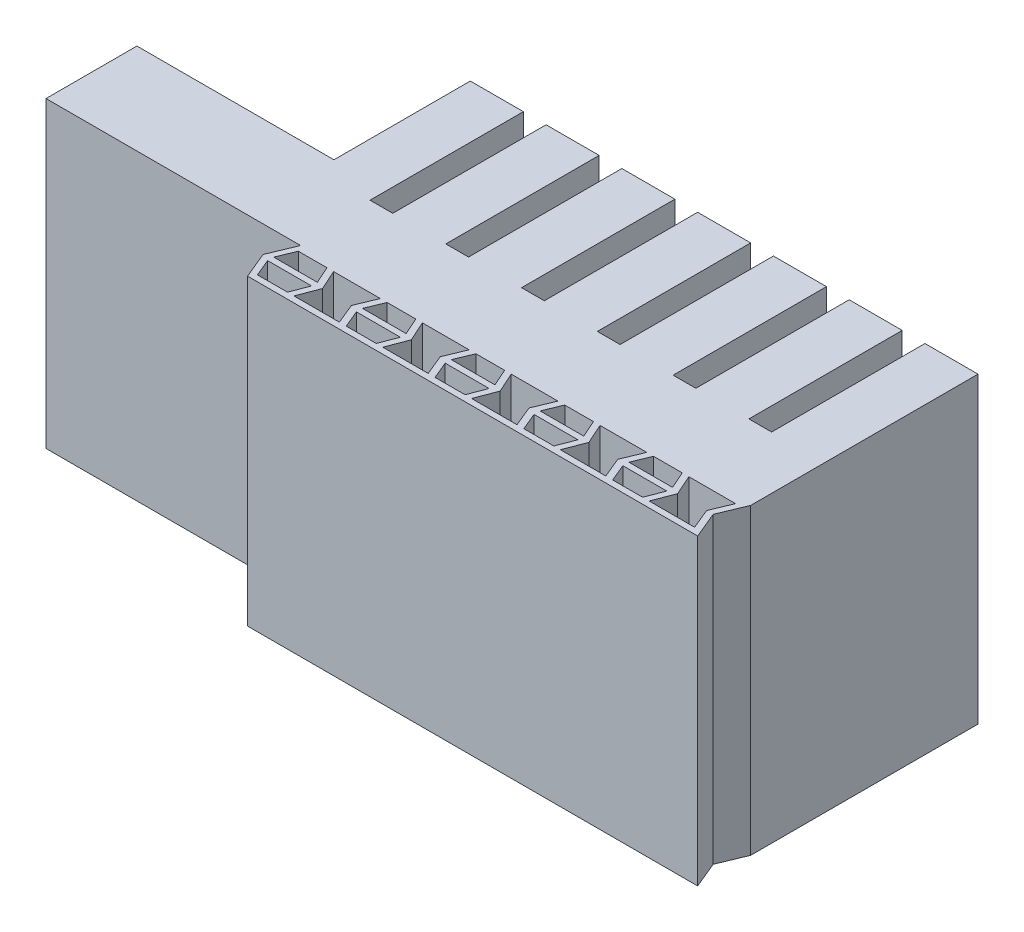
SolidWorks part; units mm, degrees
ref_plane "Front Plane" through (0, 0, 0) normal (0, 0, 1) x (1, 0, 0)
ref_plane "Top Plane" through (0, 0, 0) normal (0, 1, 0) x (1, 0, 0)
ref_plane "Right Plane" through (0, 0, 0) normal (1, 0, 0) x (0, 0, -1)
sketch "Sketch2" plane through (0, 0, 0) normal (0, 1, 0) x (1, 0, 0)
  line L0 (36, 15) -> (36, 4.8815)
  line L1 (0, 0) -> (39.5, 0)
  line L2 (0, 0) -> (0, 6)
  line L4 (39.5, 0) -> (39.5, 15)
  line L5 (34.5, 15) -> (34.5, 4.8815)
  line L6 (31, 15) -> (31, 4.8815)
  line L7 (29.5, 15) -> (29.5, 4.8815)
  line L8 (26, 15) -> (26, 4.8815)
  line L9 (24.5, 15) -> (24.5, 4.8815)
  line L10 (21, 15) -> (21, 4.8815)
  line L11 (19.5, 15) -> (19.5, 4.8815)
  line L12 (16, 15) -> (16, 4.8815)
  line L13 (14.5, 15) -> (14.5, 4.8815)
  line L14 (11, 15) -> (11, 4.8815)
  line L15 (14.5, 4.8815) -> (16, 4.8815)
  line L16 (19.5, 4.8815) -> (21, 4.8815)
  line L17 (24.5, 4.8815) -> (26, 4.8815)
  line L18 (29.5, 4.8815) -> (31, 4.8815)
  line L19 (34.5, 4.8815) -> (36, 4.8815)
  line L20 (9.5, 15) -> (9.5, 4.8815)
  line L21 (9.5, 4.8815) -> (11, 4.8815)
  line L22 (6, 15) -> (6, 6)
  line L23 (11, 15) -> (14.5, 15)
  line L24 (16, 15) -> (19.5, 15)
  line L25 (21, 15) -> (24.5, 15)
  line L26 (26, 15) -> (29.5, 15)
  line L27 (31, 15) -> (34.5, 15)
  line L28 (36, 15) -> (39.5, 15)
  line L30 (4.5, 6) -> (6, 6)
  line L31 (6, 15) -> (9.5, 15)
  line L32 (4.5, 6) -> (0, 6)
  dimension "D2" = 39.5
  dimension "D3" = 3.5
  dimension "D4" = 1.5
  dimension "D5" = 3.5
  dimension "D6" = 1.5
  dimension "D7" = 3.5
  dimension "D8" = 1.5
  dimension "D9" = 3.5
  dimension "D10" = 1.5
  dimension "D11" = 3.5
  dimension "D12" = 1.5
  dimension "D13" = 3.5
  dimension "D14" = 1.5
  dimension "D15" = 3.5
  dimension "D16" = 1.5
  dimension "D17" = 6
extrude "Boss-Extrude1" add sketch "Sketch2" along normal blind 1.1
sketch "Sketch3" plane through (0, 1.1, 0) normal (0, 1, 0) x (1, 0, 0)
  line L90 (7.1, 4.9) -> (7.1, 1.1)
  line L92 (6, 6) -> (0, 6)
  line L93 (0, 6) -> (0, 0)
  line L94 (0, 0) -> (39.5, 0)
  line L95 (39.5, 0) -> (39.5, 15)
  line L96 (39.5, 15) -> (36, 15)
  line L97 (36, 15) -> (36, 4.8815)
  line L98 (36, 4.8815) -> (34.5, 4.8815)
  line L99 (34.5, 4.8815) -> (34.5, 15)
  line L100 (34.5, 15) -> (31, 15)
  line L101 (31, 15) -> (31, 4.8815)
  line L102 (31, 4.8815) -> (29.5, 4.8815)
  line L103 (29.5, 4.8815) -> (29.5, 15)
  line L104 (29.5, 15) -> (26, 15)
  line L105 (26, 15) -> (26, 4.8815)
  line L106 (26, 4.8815) -> (24.5, 4.8815)
  line L107 (24.5, 4.8815) -> (24.5, 15)
  line L108 (24.5, 15) -> (21, 15)
  line L109 (21, 15) -> (21, 4.8815)
  line L110 (21, 4.8815) -> (19.5, 4.8815)
  line L111 (21, 4.8815) -> (19.5, 4.8815) construction
  line L112 (19.5, 4.8815) -> (19.5, 15)
  line L113 (19.5, 15) -> (16, 15)
  line L114 (16, 15) -> (16, 4.8815)
  line L115 (16, 4.8815) -> (14.5, 4.8815)
  line L116 (14.5, 4.8815) -> (14.5, 15)
  line L117 (14.5, 15) -> (11, 15)
  line L118 (11, 15) -> (11, 4.8815)
  line L119 (11, 4.8815) -> (9.5, 4.8815)
  line L120 (1.1, 4.9) -> (1.1, 1.1)
  line L121 (1.1, 1.1) -> (38.4, 1.1)
  line L122 (38.4, 1.1) -> (38.4, 13.9)
  line L123 (38.4, 13.9) -> (37.1, 13.9)
  line L124 (37.1, 13.9) -> (37.1, 3.7815)
  line L125 (37.1, 3.7815) -> (33.4, 3.7815)
  line L126 (33.4, 3.7815) -> (33.4, 13.9)
  line L127 (33.4, 13.9) -> (32.1, 13.9)
  line L128 (32.1, 13.9) -> (32.1, 3.7815)
  line L129 (32.1, 3.7815) -> (28.4, 3.7815)
  line L130 (28.4, 3.7815) -> (28.4, 13.9)
  line L131 (28.4, 13.9) -> (27.1, 13.9)
  line L132 (27.1, 13.9) -> (27.1, 3.7815)
  line L133 (27.1, 3.7815) -> (23.4, 3.7815)
  line L134 (23.4, 3.7815) -> (23.4, 13.9)
  line L135 (23.4, 13.9) -> (22.1, 13.9)
  line L136 (22.1, 13.9) -> (22.1, 3.7815)
  line L137 (22.1, 3.7815) -> (18.4, 3.7815)
  line L138 (18.4, 3.7815) -> (18.4, 13.9)
  line L139 (18.4, 13.9) -> (17.1, 13.9)
  line L140 (17.1, 13.9) -> (17.1, 3.7815)
  line L141 (17.1, 3.7815) -> (13.4, 3.7815)
  line L142 (13.4, 3.7815) -> (13.4, 13.9)
  line L143 (13.4, 13.9) -> (12.1, 13.9)
  line L144 (12.1, 13.9) -> (12.1, 3.7815)
  line L145 (12.1, 3.7815) -> (8.4, 3.7815)
  line L146 (8.4, 3.7815) -> (8.4, 13.9)
  line L147 (8.4, 13.9) -> (7.1, 13.9)
  line L148 (7.1, 13.9) -> (7.1, 4.9)
  line L149 (7.1, 4.9) -> (1.1, 4.9)
  line L151 (7.1, 1.1) -> (38.4, 1.1)
  line L152 (38.4, 1.1) -> (38.4, 13.9)
  line L153 (38.4, 13.9) -> (37.1, 13.9)
  line L154 (37.1, 13.9) -> (37.1, 3.7815)
  line L155 (37.1, 3.7815) -> (33.4, 3.7815)
  line L156 (33.4, 3.7815) -> (33.4, 13.9)
  line L157 (33.4, 13.9) -> (32.1, 13.9)
  line L158 (32.1, 13.9) -> (32.1, 3.7815)
  line L159 (32.1, 3.7815) -> (28.4, 3.7815)
  line L160 (28.4, 3.7815) -> (28.4, 13.9)
  line L161 (28.4, 13.9) -> (27.1, 13.9)
  line L162 (27.1, 13.9) -> (27.1, 3.7815)
  line L163 (27.1, 3.7815) -> (23.4, 3.7815)
  line L164 (23.4, 3.7815) -> (23.4, 13.9)
  line L165 (23.4, 13.9) -> (22.1, 13.9)
  line L166 (22.1, 13.9) -> (22.1, 3.7815)
  line L167 (22.1, 3.7815) -> (18.4, 3.7815)
  line L168 (18.4, 3.7815) -> (18.4, 13.9)
  line L169 (18.4, 13.9) -> (17.1, 13.9)
  line L170 (17.1, 13.9) -> (17.1, 3.7815)
  line L171 (17.1, 3.7815) -> (13.4, 3.7815)
  line L172 (13.4, 3.7815) -> (13.4, 13.9)
  line L173 (13.4, 13.9) -> (12.1, 13.9)
  line L174 (12.1, 13.9) -> (12.1, 3.7815)
  line L175 (12.1, 3.7815) -> (8.4, 3.7815)
  line L176 (8.4, 3.7815) -> (8.4, 13.9)
  line L177 (8.4, 13.9) -> (7.1, 13.9)
  line L178 (7.1, 13.9) -> (7.1, 4.9)
  line L180 (9.5, 4.8815) -> (9.5, 15)
  line L181 (9.5, 15) -> (6, 15)
  line L182 (6, 15) -> (6, 6)
  dimension "D1" = 1.1
extrude "Boss-Extrude2" add sketch "Sketch3" along normal blind 17.8
sketch "Sketch4" plane through (0, 18.9, 0) normal (0, 1, 0) x (1, 0, 0)
  line L0 (0, 6) -> (0, 0)
  line L1 (0, 0) -> (39.5, 0)
  line L2 (39.5, 0) -> (39.5, 15)
  line L3 (39.5, 15) -> (36, 15)
  line L4 (36, 15) -> (36, 4.8815)
  line L5 (36, 4.8815) -> (34.5, 4.8815)
  line L6 (34.5, 4.8815) -> (34.5, 15)
  line L7 (34.5, 15) -> (31, 15)
  line L8 (31, 15) -> (31, 4.8815)
  line L9 (31, 4.8815) -> (29.5, 4.8815)
  line L10 (29.5, 4.8815) -> (29.5, 15)
  line L11 (29.5, 15) -> (26, 15)
  line L12 (26, 15) -> (26, 4.8815)
  line L13 (26, 4.8815) -> (24.5, 4.8815)
  line L14 (24.5, 4.8815) -> (24.5, 15)
  line L15 (24.5, 15) -> (21, 15)
  line L16 (21, 15) -> (21, 4.8815)
  line L17 (21, 4.8815) -> (19.5, 4.8815)
  line L18 (19.5, 4.8815) -> (19.5, 15) construction
  line L19 (21, 4.8815) -> (19.5, 4.8815) construction
  line L20 (19.5, 4.8815) -> (19.5, 15)
  line L21 (19.5, 15) -> (16, 15)
  line L22 (16, 15) -> (16, 4.8815)
  line L23 (16, 15) -> (16, 4.8815) construction
  line L24 (16, 4.8815) -> (14.5, 4.8815)
  line L25 (14.5, 4.8815) -> (14.5, 15)
  line L26 (14.5, 15) -> (11, 15)
  line L27 (11, 15) -> (11, 4.8815)
  line L28 (11, 4.8815) -> (9.5, 4.8815)
  line L29 (9.5, 4.8815) -> (9.5, 15)
  line L30 (9.5, 15) -> (6, 15)
  line L31 (6, 15) -> (6, 6)
  line L32 (6, 6) -> (0, 6)
extrude "Boss-Extrude3" add sketch "Sketch4" along normal blind 1.1
sketch "Sketch5" plane through (0, 0, 0) normal (0, -1, 0) x (1, 0, 0)
  line L0 (0, 0) -> (39.5, 0) construction
  line L1 (39.5, 0) -> (33.4401, 0)
  line L3 (39.5, 3.5) -> (33.4401, 3.5)
  line L5 (39.5, 0) -> (39.5, -15) construction
  line L6 (39.5, 0) -> (38.7751, 1.75)
  line L7 (38.7751, 1.75) -> (39.5, 3.5)
  line L8 (39.5, 3.5) -> (39.5, 0)
  line L9 (35.4734, 3.1) -> (35.9111, 1.95)
  line L10 (35.8975, 1.55) -> (35.3816, 0.4)
  line L12 (35.4734, 3.1) -> (33.4909, 3.1)
  line L13 (36.42, 1.7375) -> (35.82, 0.4)
  line L14 (38.9014, 0.4) -> (35.82, 0.4)
  line L15 (38.9014, 0.4) -> (38.3422, 1.75)
  line L16 (38.3422, 1.75) -> (38.9014, 3.1)
  line L17 (38.9014, 3.1) -> (35.9014, 3.1)
  line L18 (35.9014, 3.1) -> (36.42, 1.7375)
  line L19 (35.6949, 3.6423) -> (36.42, 1.7375) construction
  line L20 (33.4909, 3.1) -> (33.0146, 1.95)
  line L21 (38.9014, 3.1) -> (29.2666, 3.1) construction
  line L22 (36.42, 1.7375) -> (35.5671, -0.1637) construction
  line L23 (33.0146, 1.55) -> (33.4909, 0.4)
  line L24 (38.9014, 0.4) -> (29.2666, 0.4) construction
  line L25 (33.4909, 0.4) -> (34.8164, 0.4)
  line L26 (33.4401, 3.5) -> (32.7153, 1.75)
  line L27 (33.0146, 1.95) -> (35.9111, 1.95)
  line L28 (34.7414, 3.1) -> (35.4734, 3.1)
  line L29 (34.8164, 0.4) -> (35.3816, 0.4)
  line L30 (35.8975, 1.55) -> (33.0146, 1.55)
  line L31 (35.3211, 3.5) -> (35.9872, 1.75) construction
  line L32 (35.9872, 1.75) -> (35.2022, 0) construction
  line L33 (32.7153, 1.75) -> (33.4401, 0)
  line L34 (39.5, 3.5) -> (29.2666, 3.5) construction
  line L35 (39.5, 0) -> (29.2666, 0) construction
  line M55 (39.5, 0) -> (0, 0)
  dimension "D1" = 3.5
  dimension "D2" = 1.75
  dimension "D3" = 135
  dimension "D4" = 0.4
  dimension "D5" = 0.2
  dimension "D6" = 0.4
  dimension "D7" = 135
  dimension "D8" = 0.4
  dimension "D9" = 1.75
  dimension "D10" = 0.2
  dimension "D11" = 3
  dimension "D12" = 135
  dimension "D13" = 0.4
extrude "Boss-Extrude4" add sketch "Sketch5" against normal up to surface (20 mm away) contours L26 L33 L6 L7 L3 L18 L17 L16 L15 L14 L13 L27 L20 L12 L9 L30 L10 L29 L25 L23 M55 up to face at (21.2333, 20, -9.3526)
pattern_linear "LPattern1" count 5 spacing 5.86 along (-1, 0, 0) of "Boss-Extrude4"
sketch "Sketch6" plane through (0, 0, 0) normal (0, -1, 0) x (1, 0, 0)
  line L0 (10.0001, 3.5) -> (9.8001, 3.5)
  line L1 (9.8001, 3.5) -> (9.0753, 1.75)
  line L2 (9.0753, 1.75) -> (9.8001, 0)
  line L3 (0, 0) -> (10.0001, 0) construction
  line L4 (10.0001, 3.5) -> (9.2753, 1.75)
  line L5 (9.2753, 1.75) -> (10.0001, 0)
  line L6 (10.0001, 0) -> (9.8001, 0)
  dimension "D1" = 1.75
  dimension "D2" = 135
  dimension "D3" = 0.2
extrude "Boss-Extrude5" add sketch "Sketch6" against normal up to surface (20 mm away)
sketch "Sketch7" plane through (0, 0, 0) normal (-1, 0, 0) x (0, 0, 1)
  line L1 (0, 20) -> (-6, 20)
  line L2 (0, 20) -> (0, 0)
  line L3 (0, 0) -> (-6, 0)
  line L4 (-6, 20) -> (-6, 0)
extrude "Boss-Extrude6" add sketch "Sketch7" along normal blind 7
sketch "Sketch8" plane through (-7, 0, 0) normal (-1, 0, 0) x (0, 0, 1)
  line L0 (-6, 0) -> (0, 0) construction
  line L1 (0, 20) -> (0, 0) construction
  circle A0 centre (-3, 10) radius 2.075
  dimension "D1" = 4.15
  dimension "D2" = 10
  dimension "D3" = 3
extrude "Cut-Extrude1" cut sketch "Sketch8" against normal up to surface (14.1 mm away) up to face at (7.1, 10, -7.5)
sketch "Sketch9" plane through (0, 0, -6) normal (0, 0, -1) x (-1, 0, 0)
  line L0 (-6, 20) -> (-6, 0) construction
  line L1 (-6, 15.05) -> (1.2824, 15.05)
  line L2 (-6, 15.05) -> (-6, 17.95)
  line L3 (-6, 17.95) -> (1.2824, 17.95)
  line L4 (1.2824, 15.05) -> (1.2824, 17.95)
  line L5 (7, 0) -> (7, 20)
  line L6 (-6, 4.95) -> (1.2824, 4.95)
  line L7 (-6, 4.95) -> (-6, 2.05)
  line L8 (-6, 2.05) -> (1.2824, 2.05)
  line L9 (1.2824, 4.95) -> (1.2824, 2.05)
  line L10 (-6, 0) -> (7, 0) construction
  line L11 (7, 20) -> (7, 0) construction
  line L12 (7, 20) -> (7, 10)
  line M10 (-6, 20) -> (-6, 0)
  dimension "D1" = 2.9
  dimension "D2" = 2.9
  dimension "D3" = 10.1
  dimension "D4" = 5.05
extrude "Boss-Extrude7" add sketch "Sketch9" along normal blind 1.4 contours L9 L6 L8 M10 | L1 L4 L3 M10
